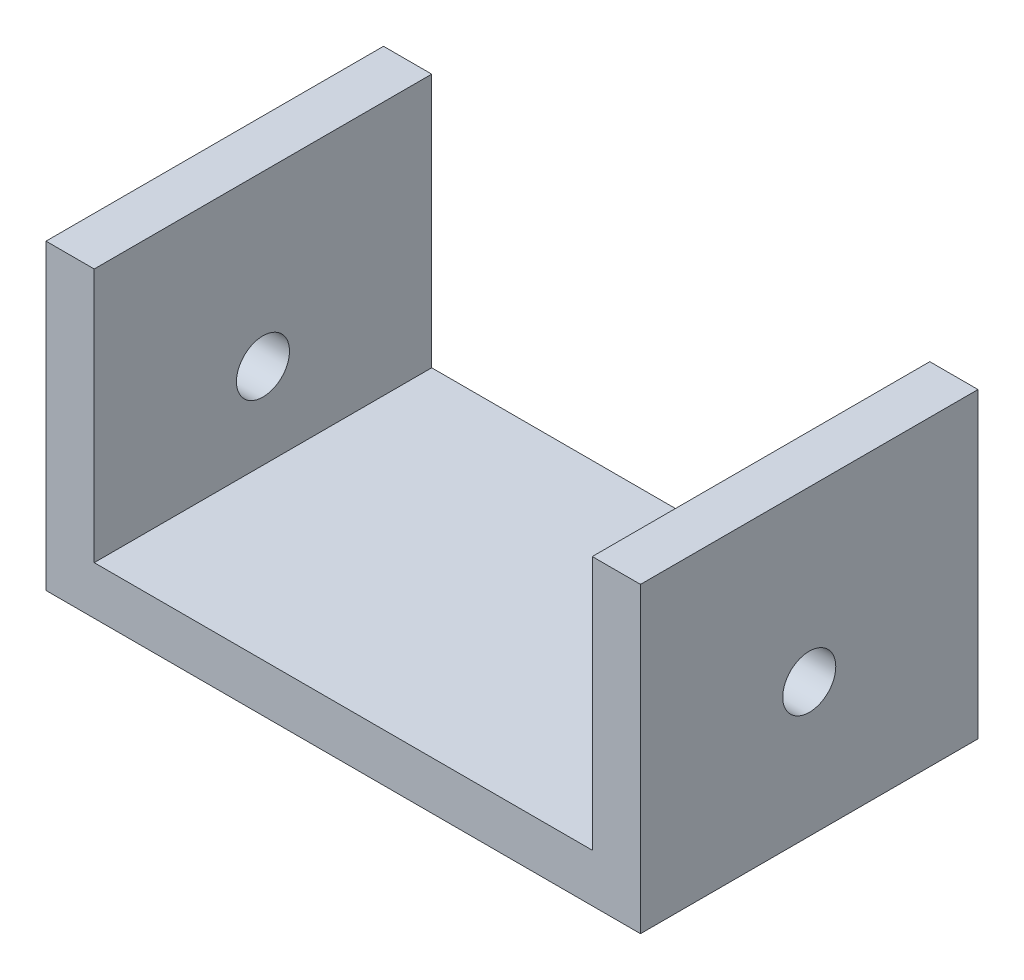
SolidWorks part; units mm, degrees
ref_plane "Front Plane" through (0, 0, 0) normal (0, 0, 1) x (1, 0, 0)
ref_plane "Top Plane" through (0, 0, 0) normal (0, 1, 0) x (1, 0, 0)
ref_plane "Right Plane" through (0, 0, 0) normal (1, 0, 0) x (0, 0, -1)
sketch "Sketch1" plane through (0, 0, 0) normal (0, 0, 1) x (1, 0, 0)
  line L1 (-30.825, 15.6875) -> (30.825, 15.6875)
  line L2 (-30.825, 15.6875) -> (-30.825, -15.6875)
  line L3 (-30.825, -15.6875) -> (30.825, -15.6875)
  line L4 (30.825, 15.6875) -> (30.825, -15.6875)
  line L5 (0, -15.6875) -> (0, 15.6875) construction
  line L6 (-30.825, 0) -> (30.825, 0) construction
  point P0 (0, 0)
  dimension "D1" = 61.65
  dimension "D2" = 31.375
extrude "Boss-Extrude1" add sketch "Sketch1" along normal blind 35
sketch "Sketch2" plane through (0, 0, 0) normal (0, 0, -1) x (-1, 0, 0)
  line L0 (-30.825, 15.6875) -> (30.825, 15.6875) construction
  line L1 (-25.825, 15.6875) -> (25.825, 15.6875)
  line L2 (-25.825, 15.6875) -> (-25.825, -10.6875)
  line L3 (-25.825, -10.6875) -> (25.825, -10.6875)
  line L4 (25.825, 15.6875) -> (25.825, -10.6875)
  line L5 (-30.825, -15.6875) -> (-30.825, 15.6875) construction
  line L6 (30.825, 15.6875) -> (30.825, -15.6875) construction
  line L7 (30.825, -15.6875) -> (-30.825, -15.6875) construction
  dimension "D1" = 5
  dimension "D2" = 5
  dimension "D3" = 5
extrude "Cut-Extrude1" cut sketch "Sketch2" against normal through all
sketch "Sketch3" plane through (30.825, 0, 0) normal (1, 0, 0) x (0, 0, -1)
  line L0 (-35, 15.6875) -> (0, 15.6875) construction
  line L1 (0, -15.6875) -> (0, 15.6875) construction
  circle A0 centre (-17.5, -1.8125) radius 2.75
  point P6 (-55.0755, 12.3429)
  dimension "D1" = 17.5
  dimension "D2" = 17.5
extrude "Cut-Extrude2" cut sketch "Sketch3" against normal through all
